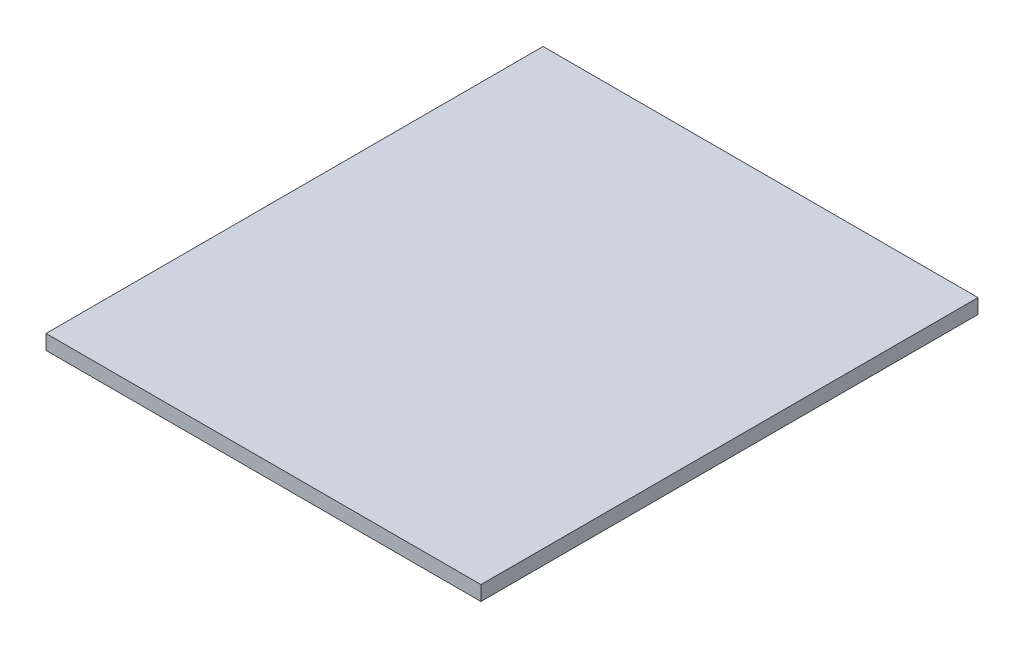
SolidWorks part; units mm, degrees
ref_plane "Front Plane" through (0, 0, 0) normal (0, 0, 1) x (1, 0, 0)
ref_plane "Top Plane" through (0, 0, 0) normal (0, 1, 0) x (1, 0, 0)
ref_plane "Right Plane" through (0, 0, 0) normal (1, 0, 0) x (0, 0, -1)
sketch "Sketch1" plane through (0, 0, 0) normal (0, 1, 0) x (1, 0, 0)
  line L1 (88.9, -101.6) -> (-88.9, -101.6)
  line L2 (88.9, -101.6) -> (88.9, 101.6)
  line L3 (88.9, 101.6) -> (-88.9, 101.6)
  line L4 (-88.9, -101.6) -> (-88.9, 101.6)
  line L5 (88.9, -101.6) -> (-88.9, 101.6) construction
  line L6 (88.9, 101.6) -> (-88.9, -101.6) construction
  point P0 (0, 0)
  dimension "D1" = 177.8
  dimension "D2" = 203.2
extrude "Boss-Extrude1" add sketch "Sketch1" along normal blind 6
